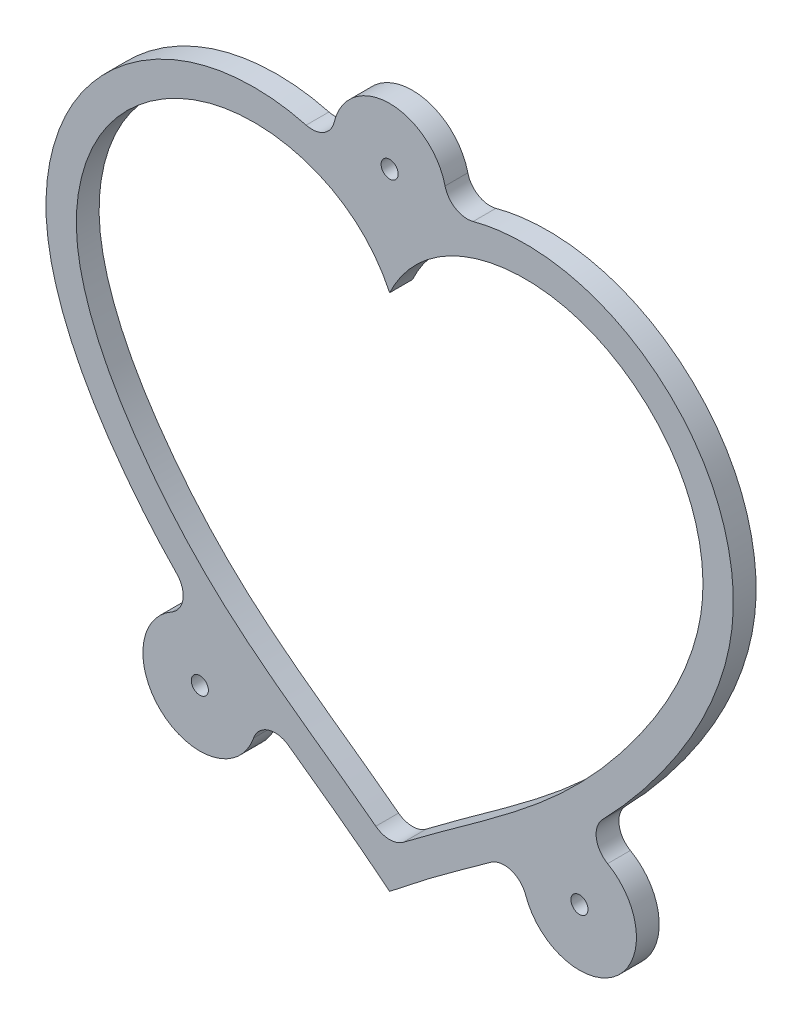
SolidWorks part; units mm, degrees
ref_plane "Plan de face" through (0, 0, 0) normal (0, 0, 1) x (1, 0, 0)
ref_plane "Plan de dessus" through (0, 0, 0) normal (0, 1, 0) x (1, 0, 0)
ref_plane "Plan de droite" through (0, 0, 0) normal (1, 0, 0) x (0, 0, -1)
sketch "Esquisse1" plane through (0, 0, 0) normal (0, 0, 1) x (1, 0, 0)
  line L0 (0, 0) -> (0, 150) construction
  dimension "D1" = 150
sketch "Esquisse2" plane through (0, 0, 0) normal (0, 0, 1) x (1, 0, 0)
  line L0 (36.6667, 114.5) -> (183.3333, 114.5) construction
sketch "Esquisse3" plane through (0, 0, 0) normal (0, 0, 1) x (1, 0, 0)
  line L0 (82.4726, 126.3503) -> (82.4726, 0) construction
  line L1 (0, 0) -> (0, 150) construction
  spline S0 degree 3 poles (82.4726, 0) (67.9439, 11.5192) (42.5777, 27.1597) (17.2808, 55.9474) (4.1683, 78.1076) (-1.8917, 100.904) (4.3812, 128.2947) (38.368, 154.8544) (73.8786, 144.5963) (82.4726, 126.3503) knots 0 0 0 0 0.223856 0.354281 0.457435 0.531451 0.633256 0.777211 1 1 1 1
  spline S1 degree 3 poles (82.4726, 0) (97.0014, 11.5192) (122.3675, 27.1597) (147.6645, 55.9474) (160.7769, 78.1076) (166.837, 100.904) (160.564, 128.2947) (126.5773, 154.8544) (91.0666, 144.5963) (82.4726, 126.3503) knots 0 0 0 0 0.223856 0.354281 0.457435 0.531451 0.633256 0.777211 1 1 1 1
sketch "Esquisse4" plane through (0, 0, 0) normal (0, 0, 1) x (1, 0, 0)
  spline S0 degree 3 poles (1727.411, -2489.0683) (-284.2958, 16.1838) (27.4489, -80.8569) (147.6645, 55.9474) (160.7769, 78.1076) (166.837, 100.904) (160.564, 128.2947) (47.3698, 216.7528) (-199.374, -191.7326) (2806.6423, -1073.4289) knots -1.716378 -1.716378 -1.716378 -1.716378 0.223856 0.354281 0.457435 0.531451 0.633256 0.777211 2.091971 2.091971 2.091971 2.091971 only from (82.4726, 0) to (82.4726, 126.3503) construction
  spline S1 degree 3 poles (-1562.4657, -2489.0683) (449.241, 16.1838) (137.4964, -80.8569) (17.2808, 55.9474) (4.1683, 78.1076) (-1.8917, 100.904) (4.3812, 128.2947) (117.5754, 216.7528) (364.3193, -191.7326) (-2641.6971, -1073.4289) knots -1.716378 -1.716378 -1.716378 -1.716378 0.223856 0.354281 0.457435 0.531451 0.633256 0.777211 2.091971 2.091971 2.091971 2.091971 only from (82.4726, 0) to (82.4726, 126.3503) construction
  spline S2 degree 3 poles (82.4726, 0) (97.0014, 11.5192) (122.3675, 27.1597) (147.6645, 55.9474) (160.7769, 78.1076) (166.837, 100.904) (160.564, 128.2947) (126.5773, 154.8544) (91.0666, 144.5963) (82.4726, 126.3503) knots 0 0 0 0 0.223856 0.354281 0.457435 0.531451 0.633256 0.777211 1 1 1 1
  spline S3 degree 3 poles (82.4726, 0) (67.9439, 11.5192) (42.5777, 27.1597) (17.2808, 55.9474) (4.1683, 78.1076) (-1.8917, 100.904) (4.3812, 128.2947) (38.368, 154.8544) (73.8786, 144.5963) (82.4726, 126.3503) knots 0 0 0 0 0.223856 0.354281 0.457435 0.531451 0.633256 0.777211 1 1 1 1
  spline S4 degree 1 poles (82.4726, -10.2094) (82.4726, 140.5424) knots 0 0 1 1 construction
  spline S5 degree 1 poles (82.4726, -10.2094) (82.4726, 140.5424) knots 0 0 1 1 construction
  spline S6 degree 3 poles (82.4726, -10.2094) (81.4738, -9.4175) (79.9807, -8.2338) (77.9691, -6.6385) (76.027, -5.1004) (73.5796, -3.2133) (69.5873, -0.2103) (64.4913, 3.5091) (56.1803, 9.4818) (45.6535, 17.1447) (35.3269, 25.5587) (27.502, 33.0088) (20.0853, 40.8364) (13.2707, 49.2194) (7.086, 58.0743) (2.7709, 65.072) (-1.0708, 72.4555) (-4.3137, 80.2437) (-6.8108, 88.5629) (-8.1951, 97.4252) (-8.0324, 106.5963) (-6.3307, 115.5722) (-3.1414, 124.1989) (1.558, 132.1998) (7.5191, 139.2126) (14.5352, 145.1633) (22.4231, 149.9165) (31.0332, 153.3404) (40.1305, 155.2386) (49.3559, 155.5824) (58.5004, 154.3685) (67.3054, 151.5502) (74.1289, 147.802) (79.0926, 143.9475) (81.3946, 141.7139) (82.4726, 140.5424) knots -0.025527 -0.025527 -0.025527 -0.025527 -0.010137 -0.002442 0.005253 0.020643 0.036033 0.066814 0.097594 0.159154 0.220714 0.251494 0.282274 0.343834 0.374614 0.405394 0.436174 0.466954 0.497734 0.528514 0.559294 0.590074 0.620854 0.651634 0.682415 0.713195 0.743975 0.774755 0.805535 0.836315 0.867095 0.897875 0.928655 0.944045 0.959435 0.959435 0.959435 0.959435
  spline S7 degree 3 poles (82.4726, 140.5424) (83.5506, 141.7139) (85.8527, 143.9475) (90.8163, 147.802) (97.6398, 151.5502) (106.4448, 154.3685) (115.5894, 155.5824) (124.8148, 155.2386) (133.912, 153.3404) (142.5221, 149.9165) (150.4101, 145.1633) (157.4261, 139.2126) (163.3872, 132.1998) (168.0866, 124.1989) (171.2759, 115.5722) (172.9777, 106.5963) (173.1404, 97.4252) (171.756, 88.5629) (169.2589, 80.2437) (166.0161, 72.4555) (162.1743, 65.072) (157.8593, 58.0743) (151.6746, 49.2194) (144.8599, 40.8364) (137.4432, 33.0088) (129.6183, 25.5587) (119.2917, 17.1447) (108.7649, 9.4818) (100.4539, 3.5091) (95.3579, -0.2103) (91.3656, -3.2133) (88.9182, -5.1004) (86.9761, -6.6385) (84.9645, -8.2338) (83.4715, -9.4175) (82.4726, -10.2094) knots -0.025527 -0.025527 -0.025527 -0.025527 -0.010137 0.005253 0.036033 0.066814 0.097594 0.128374 0.159154 0.189934 0.220714 0.251494 0.282274 0.313054 0.343834 0.374614 0.405394 0.436174 0.466954 0.497734 0.528514 0.559294 0.590074 0.651634 0.682415 0.713195 0.774755 0.836315 0.867095 0.897875 0.913265 0.928655 0.93635 0.944045 0.959435 0.959435 0.959435 0.959435
  dimension "D1" = 8
extrude "Boss.-Extru.1" add sketch "Esquisse4" along normal blind 6
sketch "Esquisse5" plane through (0, 0, 6) normal (0, 0, 1) x (1, 0, 0)
  line L0 (82.4726, -10.2094) -> (82.4726, 140.5424) construction
  line L1 (82.4726, 140.5424) -> (82.4726, 154.5424) construction
  circle A0 centre (32.4726, 11.7906) radius 15
  circle A1 centre (32.4726, 11.7906) radius 2.25
  circle A2 centre (132.4726, 11.7906) radius 2.25
  circle A3 centre (132.4726, 11.7906) radius 15
  circle A4 centre (82.4726, 154.5424) radius 15
  circle A5 centre (82.4726, 154.5424) radius 2.25
  dimension "D1" = 4.5
  dimension "D2" = 30
  dimension "D3" = 100
  dimension "D4" = 22
  dimension "D5" = 14
extrude "Boss.-Extru.2" add sketch "Esquisse5" against normal up to vertex (6 mm away)
fillet "Congé1" radius 6 7 edges at (82.4726, 0, 3) (67.9066, 150.9605, 3) (97.0387, 150.9605, 3) (118.2362, 16.5155, 3) (130.6445, 26.6788, 3) (34.3007, 26.6788, 3) (46.709, 16.5155, 3)
